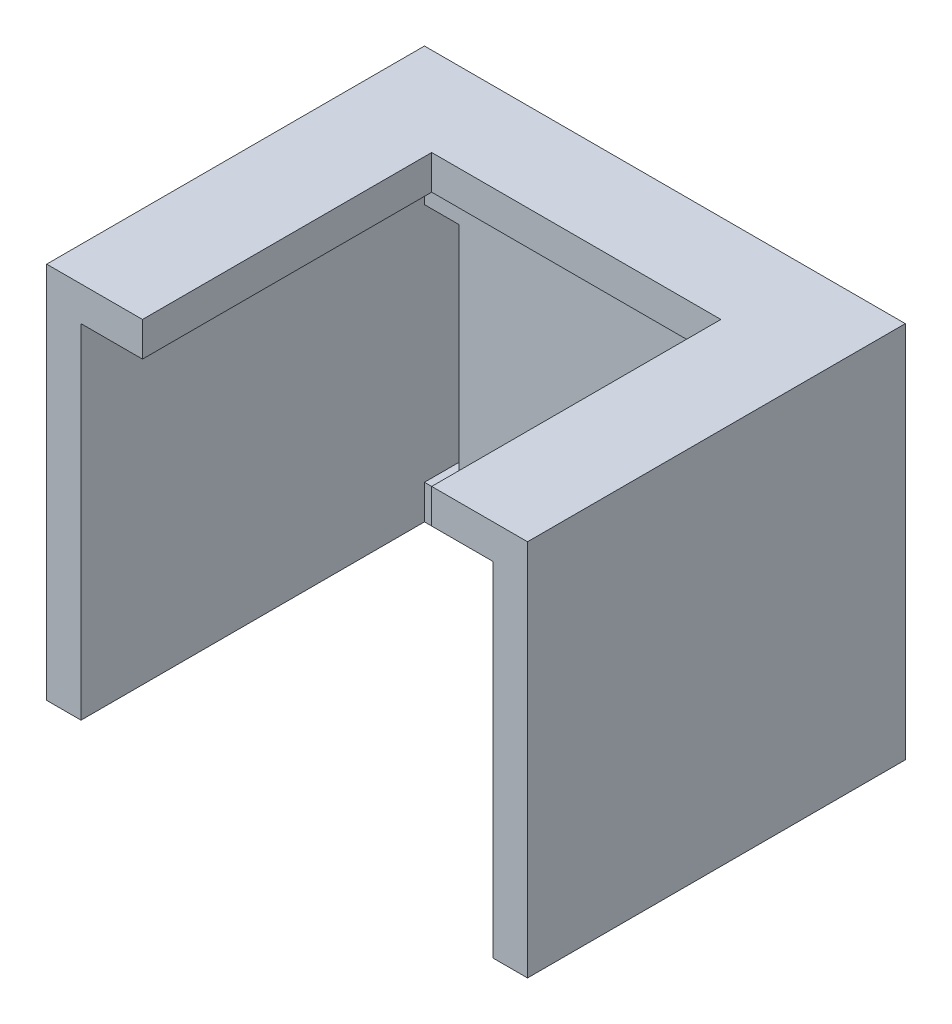
SolidWorks part; units mm, degrees
material "CA"
ref_plane "Front Plane" through (0, 0, 0) normal (0, 0, 1) x (1, 0, 0)
ref_plane "Top Plane" through (0, 0, 0) normal (0, 1, 0) x (1, 0, 0)
ref_plane "Right Plane" through (0, 0, 0) normal (1, 0, 0) x (0, 0, -1)
sketch "Sketch1" plane through (0, 0, 0) normal (0, 0, 1) x (1, 0, 0)
  line L1 (0, 0) -> (-70, 0)
  line L2 (0, 0) -> (0, 55)
  line L3 (0, 55) -> (-70, 55)
  line L4 (-70, 0) -> (-70, 55)
  dimension "D1" = 70
  dimension "D2" = 55
extrude "Boss-Extrude1" add sketch "Sketch1" along normal blind 5
sketch "Sketch2" plane through (0, 0, 5) normal (0, 0, 1) x (1, 0, 0)
  line L0 (0, 55) -> (-70, 55) construction
  line L1 (-65, 50) -> (-60, 50)
  line L2 (-65, 50) -> (-65, 5)
  line L3 (-65, 5) -> (-60, 5)
  line L4 (-60, 50) -> (-60, 5)
  line L9 (-10.0196, 50) -> (-5, 50)
  line L10 (-10.0196, 50) -> (-10.0196, 5)
  line L11 (-10.0196, 5) -> (-5, 5)
  line L12 (-5, 50) -> (-5, 5)
  line L13 (-70, 55) -> (-70, 0) construction
  line L14 (0, 0) -> (0, 55) construction
  line L15 (-70, 0) -> (0, 0) construction
  dimension "D1" = 5
  dimension "D2" = 5
  dimension "D3" = 5
  dimension "D4" = 5
  dimension "D5" = 5
  dimension "D6" = 5.0196
  dimension "D8" = 5
  dimension "D9" = 5
extrude "Cut-Extrude1" cut sketch "Sketch2" against normal blind 5
sketch "Sketch6" plane through (0, 0, 5) normal (0, 0, 1) x (1, 0, 0)
  line L0 (0, 55) -> (-70, 55) construction
  line L1 (-70, 0) -> (-65, 0)
  line L2 (-70, 0) -> (-70, 55)
  line L3 (-70, 55) -> (-65, 55)
  line L4 (-65, 0) -> (-65, 50)
  line L6 (0, 0) -> (-5, 0)
  line L7 (0, 0) -> (0, 55)
  line L8 (0, 55) -> (-5, 55)
  line L9 (-5, 0) -> (-5, 50)
  line L10 (-5, 50) -> (-65, 50)
  line L12 (-5, 55) -> (-65, 55)
  dimension "D1" = 5
extrude "Boss-Extrude4" add sketch "Sketch6" along normal blind 50
sketch "Sketch7" plane through (0, 55, 0) normal (0, 1, 0) x (1, 0, 0)
  line L0 (0, -55) -> (-70, -55) construction
  line L1 (-56.05, -55) -> (-13.95, -55)
  line L2 (-56.05, -55) -> (-56.05, -12.9)
  line L3 (-56.05, -12.9) -> (-13.95, -12.9)
  line L4 (-13.95, -55) -> (-13.95, -12.9)
  line L5 (-70, -55) -> (-70, 0) construction
  point P6 (-35, -12.9)
  dimension "D1" = 42.1
  dimension "D2" = 42.1
  dimension "D3" = 35
extrude "Cut-Extrude2" cut sketch "Sketch7" against normal blind 5
sketch "Sketch9" plane through (-60, 0, 0) normal (-1, 0, 0) x (0, 0, 1)
  line L0 (5, 5) -> (5, 50) construction
  line L1 (0, 50) -> (5, 50)
  line L2 (0, 50) -> (0, 40)
  line L3 (0, 40) -> (5, 40)
  line L4 (5, 50) -> (5, 40)
  dimension "D1" = 10
extrude "Boss-Extrude5" add sketch "Sketch9" along normal blind 5
sketch "Sketch11" plane through (-10.0196, 0, 0) normal (1, 0, 0) x (0, 0, -1)
  line L0 (-5, 50) -> (-5, 5) construction
  line L1 (0, 50) -> (-5, 50)
  line L2 (0, 50) -> (0, 40)
  line L3 (0, 40) -> (-5, 40)
  line L4 (-5, 50) -> (-5, 40)
  dimension "D1" = 10
extrude "Boss-Extrude6" add sketch "Sketch11" along normal blind 5
